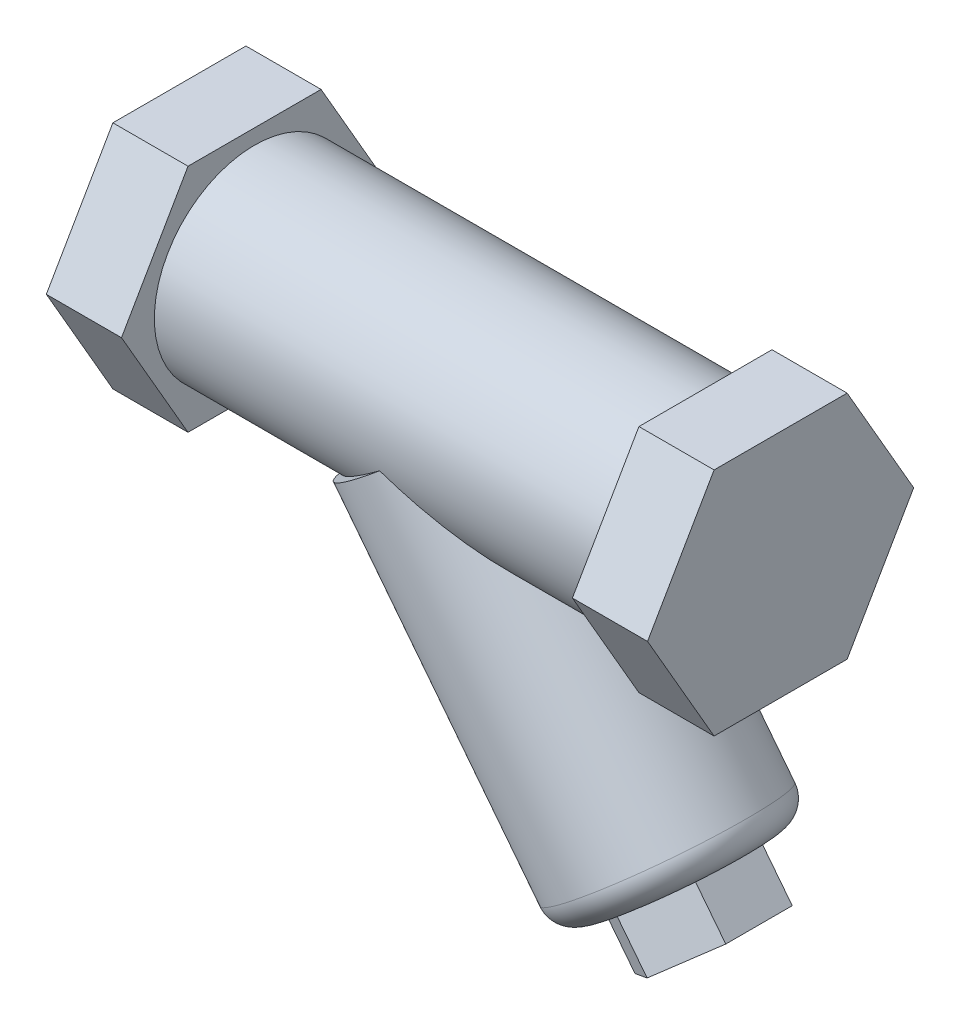
SolidWorks part; units mm, degrees
ref_plane "Плоскость1" through (0, 0, 0) normal (0, 0, 1) x (1, 0, 0)
ref_plane "Плоскость2" through (0, 0, 0) normal (0, 1, 0) x (1, 0, 0)
ref_plane "Плоскость3" through (0, 0, 0) normal (1, 0, 0) x (0, 0, -1)
sketch "Эскиз1" plane through (0, 0, 0) normal (1, 0, 0) x (0, 0, -1)
  line L1 (26.5581, 0) -> (13.2791, 23)
  line L2 (13.2791, 23) -> (-13.2791, 23)
  line L3 (-13.2791, 23) -> (-26.5581, 0)
  line L4 (-26.5581, 0) -> (-13.2791, -23)
  line L5 (-13.2791, -23) -> (13.2791, -23)
  line L6 (13.2791, -23) -> (26.5581, 0)
  circle A1 centre (0, 0) radius 23 construction
  dimension "D2" = 46
extrude "Основание-Вытянуть" add sketch "Эскиз1" along normal blind 15
sketch "Эскиз2" plane through (15, 0, 0) normal (1, 0, 0) x (0, 0, -1)
  circle A0 centre (0, 0) radius 20
  dimension "D1" = 40
extrude "Бобышка-Вытянуть1" add sketch "Эскиз2" along normal blind 90
sketch "Эскиз3" plane through (105, 0, 0) normal (1, 0, 0) x (0, 0, -1)
  line L1 (26.5581, 0) -> (13.2791, 23)
  line L2 (13.2791, 23) -> (-13.2791, 23)
  line L3 (-13.2791, 23) -> (-26.5581, 0)
  line L4 (-26.5581, 0) -> (-13.2791, -23)
  line L5 (-13.2791, -23) -> (13.2791, -23)
  line L6 (13.2791, -23) -> (26.5581, 0)
  circle A0 centre (0, 0) radius 23 construction
extrude "Бобышка-Вытянуть2" add sketch "Эскиз3" along normal blind 15
sketch "Эскиз8" plane through (0, 0, 0) normal (0, 1, 0) x (1, 0, 0)
  line L0 (0, -104.8607) -> (0, 107.2171) construction
ref_plane "Плоскость5" through (0, 0, 0) normal (-0.6157, 0.788, 0) x (0, 0, 1)
ref_plane "Плоскость6" through (24.6265, -31.5204, 0) normal (-0.6157, 0.788, 0) x (0, 0, 1)
sketch "Эскиз6" plane through (24.6265, -31.5204, 0) normal (-0.6157, 0.788, 0) x (0, 0, 1)
  circle A0 centre (0, 40) radius 20
  dimension "D1" = 40
extrude "Бобышка-Вытянуть5" add sketch "Эскиз6" against normal blind 72
sketch "Эскиз7" plane through (68.9541, -88.2572, 0) normal (0.6157, -0.788, 0) x (0, 0, -1)
  line L0 (-4.6352, 40) -> (6.1247, 40) construction
  line L1 (6.6358, 51.4935) -> (-6.6358, 51.4935)
  line L2 (-6.6358, 51.4935) -> (-13.2715, 40)
  line L3 (-13.2715, 40) -> (-6.6358, 28.5065)
  line L4 (-6.6358, 28.5065) -> (6.6358, 28.5065)
  line L5 (6.6358, 28.5065) -> (13.2715, 40)
  line L6 (13.2715, 40) -> (6.6358, 51.4935)
  circle A0 centre (0, 40) radius 11.4935 construction
  circle A1 centre (0, 40) radius 20 construction
extrude "Бобышка-Вытянуть6" add sketch "Эскиз7" along normal blind 10
fillet "Скругление5" radius 5 1 edges at (84.7143, -75.944, 0)
